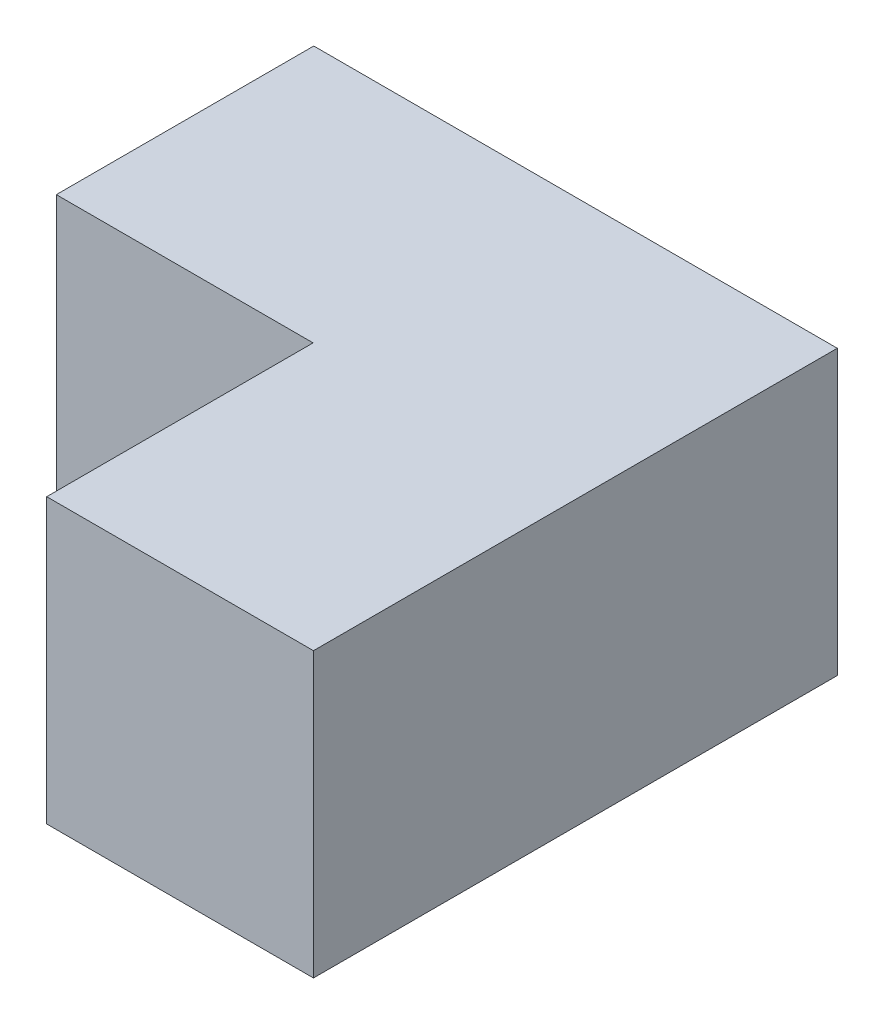
SolidWorks part; units mm, degrees
ref_plane "Front Plane" through (0, 0, 0) normal (0, 0, 1) x (1, 0, 0)
ref_plane "Top Plane" through (0, 0, 0) normal (0, 1, 0) x (1, 0, 0)
ref_plane "Right Plane" through (0, 0, 0) normal (1, 0, 0) x (0, 0, -1)
sketch "Sketch1" plane through (0, 0, 0) normal (0, 1, 0) x (1, 0, 0)
  line L0 (29, 109.5) -> (145, 109.5) construction
  line L1 (0, 0) -> (0, 116.767) construction
  line L2 (23.0118, 80.0276) -> (150.0261, 80.0276) construction
  line L3 (0, 80.0276) -> (0, 219.0676)
  line L4 (0, 219.0676) -> (103.0401, 219.0676)
  line L5 (103.0401, 219.0676) -> (103.0401, 195.9995)
  line L6 (103.0401, 195.9995) -> (23.0118, 195.9995)
  line L7 (23.0118, 195.9995) -> (23.0118, 161.0132)
  line L8 (150.0261, 80.0276) -> (150.0261, 148.0117)
  line L9 (150.0261, 148.0117) -> (172.9743, 148.0117)
  line L10 (172.9743, 80.0276) -> (172.9743, 148.0117)
  line L11 (172.9743, 80.0276) -> (175.6962, 80.0276) construction
  line L12 (103.0401, 219.0676) -> (173.9279, 219.0676) construction
  line L13 (23.0118, 136.0582) -> (23.0118, 80.0276)
  line L14 (173.9279, 219.0676) -> (173.9279, 172.1301) construction
  line L16 (173.9279, 172.1301) -> (150.0261, 172.1301)
  line L17 (173.9279, 172.1301) -> (173.9279, 219.0676)
  line L18 (173.9279, 219.0676) -> (127.0177, 219.0676)
  line L19 (127.0177, 195.9995) -> (127.0177, 219.0676)
  line L22 (127.0177, 195.9995) -> (150.0261, 195.9995)
  line L23 (150.0261, 172.1301) -> (150.0261, 195.9995)
  arc A0 (0, 80.0276) -> (172.9743, 80.0276) centre (86.4872, 86.7884) ccw
  arc A1 (23.0118, 80.0276) -> (112.0664, 28.4105) centre (86.519, 86.9649) ccw
  arc A2 (23.0118, 161.0132) -> (136.7449, 48.2112) centre (18.9852, 43.2164) cw
  arc A3 (23.0118, 136.0582) -> (112.0664, 28.4105) centre (17.0299, 40.4491) cw
  arc A4 (136.7449, 48.2112) -> (150.0261, 80.0276) centre (101.1223, 81.7615) ccw
extrude "Boss-Extrude1" add sketch "Sketch1" along normal blind 25.4
sketch "Sketch2" plane through (0, 25.4, 0) normal (0, 1, 0) x (1, 0, 0)
  line L1 (127.0177, 219.0676) -> (173.9279, 219.0676)
  line L2 (127.0177, 219.0676) -> (127.0177, 172.1301)
  line L3 (127.0177, 172.1301) -> (173.9279, 172.1301)
  line L4 (173.9279, 219.0676) -> (173.9279, 172.1301)
extrude "Cut-Extrude1" cut sketch "Sketch2" against normal through all both and the other way through all flip side to cut
